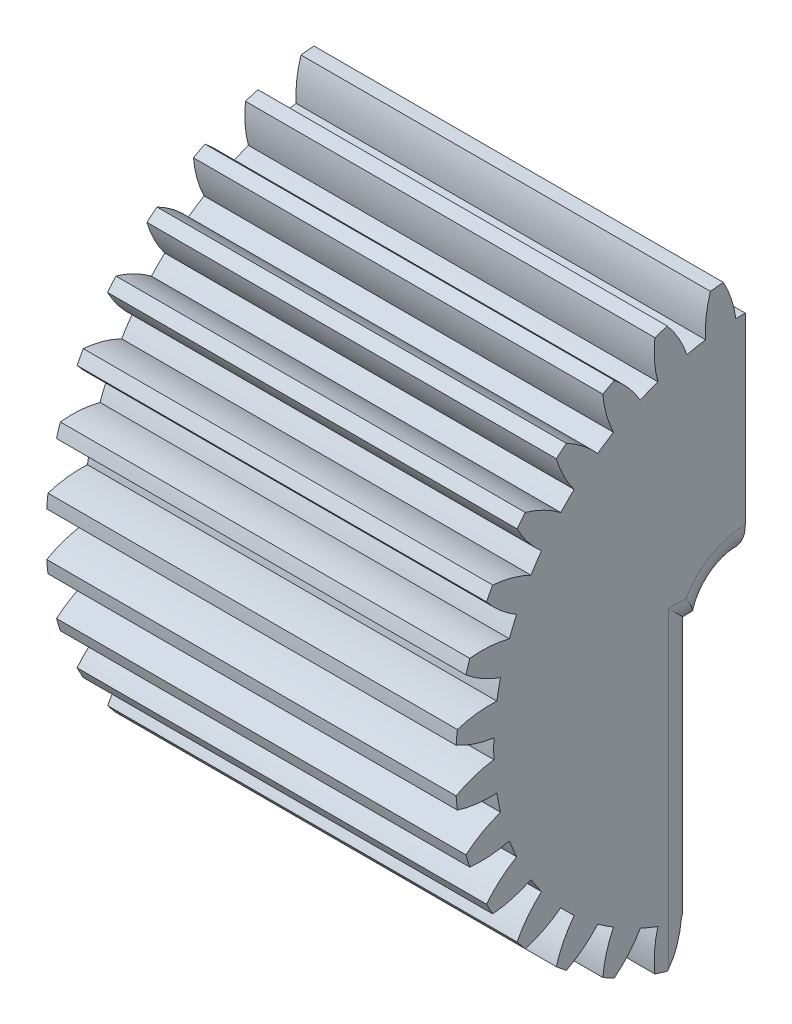
SolidWorks part; units mm, degrees
ref_plane "Plane1" through (0, 0, 0) normal (0, 0, 1) x (1, 0, 0)
ref_plane "Plane2" through (0, 0, 0) normal (0, 1, 0) x (1, 0, 0)
ref_plane "Plane3" through (0, 0, 0) normal (1, 0, 0) x (0, 0, -1)
other "Configuration Table"
sketch "HoldingSke" plane through (0, 0, 0) normal (0, 1, 0) x (1, 0, 0)
  line L0 (0, 0) -> (1.6961, -1.0598)
  line L1 (-15, 0) -> (100, 0) construction
  line L2 (0, 0) -> (-2.1039, 2.3779)
  line L3 (0, 0) -> (-11.863, 4.5341)
  line L4 (0, 0) -> (7.3237, 4.5764)
  line L5 (0, 0) -> (-46.8476, -17.4728)
  line L6 (0, 0) -> (-8.2896, -5.593)
  line L7 (-2.1039, 2.3779) -> (8.6586, 51.2059)
  line L8 (-76.2, 54.61) -> (-75.9, 54.61)
  line L9 (-67.7845, 28.3722) -> (-49.3413, 33.142)
  line L10 (-76.2, 71.12) -> (104.1128, 71.12)
  line L11 (0, 0) -> (-10, 0)
  line L12 (-76.2, 101.6) -> (-76.181, 101.6)
  line L13 (24.9733, 27.94) -> (52.9518, 28.4284)
  line L14 (24.9733, 27.94) -> (24.9743, 27.94)
  line L15 (24.9733, 27.94) -> (100.4006, 29.5858)
  line L16 (-63.627, -0.5) -> (-12.827, -0.5)
  circle A0 centre (0, 0) radius 1
  circle A1 centre (0, 0) radius 7.374
  circle A2 centre (0, 0) radius 37.5
  circle A3 centre (0, 0) radius 1
  dimension "MHD" = 14.748
  dimension "Hub_dia" = 75
  dimension "Bore" = 2
  dimension "MBD" = 2
  dimension "Num_teeth" = 32
  dimension "Pitch" = 2
  dimension "Overall_len" = 50
  dimension "Show_teeth" = 32
  dimension "Thickness" = 10
  dimension "OAL" = 50.0001
  dimension "T_dim" = 0.3
  dimension "Ap" = 14.5
  dimension "H" = 19.05
  dimension "Pitch_radius" = 180.3128
  dimension "Width" = 10
  dimension "Backlash" = 0.019
  dimension "Addendum_fac" = 1
  dimension "Dedendum_fac" = 1.25
  dimension "Clearance_fac" = 0.25
  dimension "Dedendum_add" = 0.001
  dimension "Module" = 0.5
sketch "BasProSke" plane through (0, 0, 0) normal (0, 1, 0) x (1, 0, 0)
  line L0 (-10, 0) -> (60, 0) construction
  line L1 (0, 0) -> (0, 8.5)
  line L2 (0, 0) -> (10, 0)
  line L3 (10, 0) -> (10, 8.5)
  line L4 (10, 8.5) -> (0, 8.5)
  dimension "Thickness" = 10
  dimension "Diameter" = 17
revolve "Base-Revolve" add sketch "BasProSke" angle 360 about L0
sketch "TooCutSke" plane through (0, 0, 0) normal (1, 0, 0) x (0, 0, -1)
  line L1 (0, 0) -> (0, 107) construction
  line L2 (0, 0) -> (-0.4258, 7.9887) construction
  line L3 (0, 0) -> (-1.5667, 15.9069) construction
  line L4 (-0.4258, 7.9887) -> (-0.7833, 7.9534) construction
  arc A0 (0.277, 7.3688) -> (-0.277, 7.3688) centre (0, 0) ccw
  arc A1 (0.6561, 8.5001) -> (-0.6561, 8.5001) centre (0, 0) ccw
  circle A2 centre (0, 0) radius 8 construction
  circle A3 centre (0, 0) radius 7.7452 construction
  arc A4 (-0.277, 7.3688) -> (-0.6561, 8.5001) centre (-3.4475, 6.9356) ccw
  arc A5 (0.6561, 8.5001) -> (0.277, 7.3688) centre (3.4475, 6.9356) ccw
  dimension "Root_dia" = 14.748
  dimension "Overcut_dia" = 17.0508
  dimension "Pitch_dia" = 16
  dimension "Base_dia" = 15.4904
  dimension "Flank_rad" = 3.2
  dimension "Half_ang" = 5.625
  dimension "Half_CT" = 0.3593
extrude "ToothCut" cut sketch "TooCutSke" along normal through all
fillet "Breaks" [suppressed] radius 0.01
fillet "RootFillets" [suppressed] radius 0.126
pattern_circular "TeethCuts" count 32 every 11.25 about axis through (-10, 0, 0) along (1, 0, 0) of "ToothCut", "RootFillets", "Breaks"
sketch "HubNeaOneSke" plane through (0, 0, 0) normal (-1, 0, 0) x (0, 0, 1)
  circle A0 centre (0, 0) radius 7.374
  dimension "Diameter" = 14.748
extrude "HubNearOne" [suppressed] add sketch "HubNeaOneSke" along normal blind 40.0001
sketch "HubNeaBotSke" plane through (0, 0, 0) normal (-1, 0, 0) x (0, 0, 1)
  circle A0 centre (0, 0) radius 7.374
  dimension "Diameter" = 14.748
extrude "HubNearBoth" [suppressed] add sketch "HubNeaBotSke" along normal blind 20
ref_plane "FarPln" through (10, 0, 0) normal (1, 0, 0) x (0, 0, -1)
sketch "HubFarSke" plane through (10, 0, 0) normal (1, 0, 0) x (0, 0, -1)
  circle A0 centre (0, 0) radius 7.374
  dimension "Diameter" = 14.748
extrude "HubFar" [suppressed] add sketch "HubFarSke" along normal blind 20
sketch "BorSke" plane through (0, 0, 0) normal (1, 0, 0) x (0, 0, -1)
  circle A0 centre (0, 0) radius 1
  dimension "Diameter" = 2
extrude "Bore" cut sketch "BorSke" along normal mid plane 100.0001
sketch "KeySke" plane through (0, 0, 0) normal (1, 0, 0) x (0, 0, -1)
  line L0 (-0.4, 0) -> (-0.4, 1.3)
  line L1 (-0.4, 1.3) -> (0.4, 1.3)
  line L2 (0.4, 1.3) -> (0.4, 0)
  line L3 (0, 0) -> (0, 34) construction
  line L4 (-0.4, 0) -> (0.4, 0)
  dimension "Offset" = 1.3
  dimension "Width" = 0.8
extrude "Keyway" [suppressed] cut sketch "KeySke" along normal mid plane 100.0001
pattern_circular "Keyway2" [suppressed] count 2 every 90 about axis through (-10, 0, 0) along (1, 0, 0)
sketch "Sketch1" plane through (10, 0, 0) normal (1, 0, 0) x (0, 0, -1)
  line L1 (-1.1, 0) -> (1.1, 0)
  line L2 (-1.1, 0) -> (-1.1, -12)
  line L3 (-1.1, -12) -> (1.1, -12)
  line L4 (1.1, 0) -> (1.1, -12)
  circle A0 centre (0, 0) radius 1 construction
  dimension "D3" = 12
  dimension "D1" = 2.2
  dimension "D2" = 1.1
  dimension "D4" = 12
extrude "Cut-Extrude1" cut sketch "Sketch1" against normal through all
sketch "Sketch2" plane through (0, 0, 0) normal (0, 0, 1) x (1, 0, 0)
  line L3 (3.25, 0) -> (8.75, 0)
  arc A0 (8.75, 0) -> (3.25, 0) centre (6, 0) ccw
  dimension "D2" = 5.5
  dimension "D1" = 6
revolve "Cut-Revolve1" cut sketch "Sketch2" angle 360 about L3
ref_plane "Plane4" through (3, 0, 0) normal (-1, 0, 0) x (0, 0, 1)
sketch "Sketch4" plane through (3, 0, 0) normal (-1, 0, 0) x (0, 0, 1)
  circle A0 centre (0, 0) radius 1.125
  circle A1 centre (0, 0) radius 0.5
  dimension "D1" = 1
extrude "Boss-Extrude1" add sketch "Sketch4" along normal blind 0.5
sketch "Sketch5" plane through (0, 0, -1.1) normal (0, 0, 1) x (1, 0, 0)
  line L0 (0, -8.1488) -> (10, -8.1488) construction
  line L1 (0, 0) -> (2.5, 0)
  line L2 (0, 0) -> (0, -8.1488)
  line L3 (0, -8.1488) -> (2.5, -8.1488)
  line L4 (2.5, 0) -> (2.5, -8.1488)
  dimension "D1" = 2.5
extrude "Boss-Extrude2" add sketch "Sketch5" along normal up to next
sketch "Sketch6" plane through (0, 0, 0) normal (-1, 0, 0) x (0, 0, 1)
  line L0 (1, 0) -> (-1, 0) construction
  circle A0 centre (0, 0) radius 2.25
  dimension "D1" = 4.5
extrude "Cut-Extrude4" cut sketch "Sketch6" against normal blind 2.45
sketch "Sketch7" plane through (2.5, 0, 0) normal (1, 0, 0) x (0, 0, -1)
  circle A0 centre (0, 0) radius 0.5
extrude "Cut-Extrude5" cut sketch "Sketch7" against normal blind 2.4
sketch "Sketch8" plane through (0, 0, 0) normal (0, 0, 1) x (1, 0, 0)
  line L0 (0, 0.277) -> (0, -0.277) construction
  line L1 (-0.5, 9) -> (10.5, 9)
  line L2 (-0.5, 9) -> (-0.5, -9)
  line L3 (-0.5, -9) -> (10.5, -9)
  line L4 (10.5, 9) -> (10.5, -9)
  point P6 (0, 0)
  dimension "D1" = 11
  dimension "D2" = 18
  dimension "D3" = 0.5
  dimension "D4" = 9
extrude "Cut-Extrude6" cut sketch "Sketch8" against normal blind 10
sketch "Sketch9" plane through (0, 0, 0) normal (0, 0, -1) x (-1, 0, 0)
  line L0 (-10, 1) -> (-10, 7.374) construction
  line L1 (-8.5, 5.75) -> (-6.5, 5.75)
  line L2 (-8.5, 5.75) -> (-8.5, 3.75)
  line L3 (-8.5, 3.75) -> (-6.5, 3.75)
  line L4 (-6.5, 5.75) -> (-6.5, 3.75)
  line L5 (-3.5, 5.75) -> (-1.5, 5.75)
  line L6 (-3.5, 5.75) -> (-3.5, 3.75)
  line L7 (-3.5, 3.75) -> (-1.5, 3.75)
  line L8 (-1.5, 5.75) -> (-1.5, 3.75)
  line L9 (0, -2.25) -> (0, 2.25) construction
  line L10 (0, 7.374) -> (0, 2.25) construction
  point P12 (0, 0)
  dimension "D1" = 2
  dimension "D2" = 2
  dimension "D3" = 2
  dimension "D4" = 2
  dimension "D5" = 1.5
  dimension "D6" = 3.75
  dimension "D7" = 3.75
  dimension "D8" = 1.5
extrude "Boss-Extrude3" add sketch "Sketch9" along normal blind 2
sketch "Sketch10" plane through (10, 0, 0) normal (1, 0, 0) x (0, 0, -1)
  line L1 (0, 0) -> (-1.25, 0)
  line L2 (0, 0) -> (0, -9)
  line L3 (0, -9) -> (-1.25, -9)
  line L4 (-1.25, 0) -> (-1.25, -9)
  dimension "D1" = 1.25
  dimension "D2" = 9
extrude "Cut-Extrude7" cut sketch "Sketch10" against normal blind 7
ref_plane "Plane5" through (12, 0, 0) normal (1, 0, 0) x (0, 0, -1)
sketch "Sketch11" plane through (12, 0, 0) normal (1, 0, 0) x (0, 0, -1)
  line L0 (-1.25, 0) -> (-1.25, -7.2673) construction
  line L1 (-1, 0) -> (-1.25, 0) construction
  line L2 (0, 1) -> (0, 7.374) construction
  line L3 (-1.25, 0) -> (-1.25, -7.2673)
  line L4 (-1, 0) -> (-1.25, 0)
  line L5 (0, 1) -> (0, 7.374)
  arc A0 (-2.2837, 8.1875) -> (-2.6499, 8.0764) centre (0, 0) ccw construction
  arc A1 (-0.6425, 8.4757) -> (-1.0233, 8.4382) centre (0, 0) ccw construction
  arc A2 (-1.1659, 7.2812) -> (-1.7093, 7.1732) centre (0, 0) ccw construction
  arc A3 (-3.8371, 7.5846) -> (-4.1746, 7.4042) centre (0, 0) ccw construction
  arc A4 (-2.564, 6.9139) -> (-3.0758, 6.7019) centre (0, 0) ccw construction
  arc A5 (-3.8636, 6.2808) -> (-4.3242, 5.973) centre (0, 0) ccw construction
  arc A6 (-5.2431, 6.6903) -> (-5.5389, 6.4475) centre (0, 0) ccw construction
  arc A7 (-5.0147, 5.4064) -> (-5.4064, 5.0147) centre (0, 0) ccw construction
  arc A8 (-6.4475, 5.5389) -> (-6.6903, 5.2431) centre (0, 0) ccw construction
  arc A9 (-7.4042, 4.1746) -> (-7.5846, 3.8371) centre (0, 0) ccw construction
  arc A10 (-5.973, 4.3242) -> (-6.2808, 3.8636) centre (0, 0) ccw construction
  arc A11 (-6.7019, 3.0758) -> (-6.9139, 2.564) centre (0, 0) ccw construction
  arc A12 (-8.0764, 2.6499) -> (-8.1875, 2.2837) centre (0, 0) ccw construction
  arc A13 (-7.1732, 1.7093) -> (-7.2812, 1.1659) centre (0, 0) ccw construction
  arc A14 (-8.4382, 1.0233) -> (-8.4757, 0.6425) centre (0, 0) ccw construction
  arc A15 (-7.3688, 0.277) -> (-7.3688, -0.277) centre (0, 0) ccw construction
  arc A16 (-8.4757, -0.6425) -> (-8.4382, -1.0233) centre (0, 0) ccw construction
  arc A17 (-7.2812, -1.1659) -> (-7.1732, -1.7093) centre (0, 0) ccw construction
  arc A18 (-8.1875, -2.2837) -> (-8.0764, -2.6499) centre (0, 0) ccw construction
  arc A19 (-6.9139, -2.564) -> (-6.7019, -3.0758) centre (0, 0) ccw construction
  arc A20 (-7.5846, -3.8371) -> (-7.4042, -4.1746) centre (0, 0) ccw construction
  arc A21 (-6.2808, -3.8636) -> (-5.973, -4.3242) centre (0, 0) ccw construction
  arc A22 (-6.6903, -5.2431) -> (-6.4475, -5.5389) centre (0, 0) ccw construction
  arc A23 (-5.4064, -5.0147) -> (-5.0147, -5.4064) centre (0, 0) ccw construction
  arc A24 (-5.5389, -6.4475) -> (-5.2431, -6.6903) centre (0, 0) ccw construction
  arc A25 (-4.3242, -5.973) -> (-3.8636, -6.2808) centre (0, 0) ccw construction
  arc A26 (-4.1746, -7.4042) -> (-3.8371, -7.5846) centre (0, 0) ccw construction
  arc A27 (-3.0758, -6.7019) -> (-2.564, -6.9139) centre (0, 0) ccw construction
  arc A28 (-1.7093, -7.1732) -> (-1.25, -7.2673) centre (0, 0) ccw construction
  arc A29 (-2.6499, -8.0764) -> (-2.2837, -8.1875) centre (0, 0) ccw construction
  arc A30 (-2.2837, -8.1875) -> (-1.7093, -7.1732) centre (-4.7344, -6.1297) ccw construction
  arc A31 (-2.564, -6.9139) -> (-2.6499, -8.0764) centre (0.531, -7.727) ccw construction
  arc A32 (-3.8371, -7.5846) -> (-3.0758, -6.7019) centre (-5.8392, -5.0883) ccw construction
  arc A33 (-3.8636, -6.2808) -> (-4.1746, -7.4042) centre (-0.9867, -7.6821) ccw construction
  arc A34 (-5.2431, -6.6903) -> (-4.3242, -5.973) centre (-6.7197, -3.8514) ccw construction
  arc A35 (-5.0147, -5.4064) -> (-5.5389, -6.4475) centre (-2.4664, -7.342) ccw construction
  arc A36 (-6.4475, -5.5389) -> (-5.4064, -5.0147) centre (-7.342, -2.4664) ccw construction
  arc A37 (-5.973, -4.3242) -> (-6.6903, -5.2431) centre (-3.8514, -6.7197) ccw construction
  arc A38 (-7.4042, -4.1746) -> (-6.2808, -3.8636) centre (-7.6821, -0.9867) ccw construction
  arc A39 (-6.7019, -3.0758) -> (-7.5846, -3.8371) centre (-5.0883, -5.8392) ccw construction
  arc A40 (-8.0764, -2.6499) -> (-6.9139, -2.564) centre (-7.727, 0.531) ccw construction
  arc A41 (-7.1732, -1.7093) -> (-8.1875, -2.2837) centre (-6.1297, -4.7344) ccw construction
  arc A42 (-8.4382, -1.0233) -> (-7.2812, -1.1659) centre (-7.4749, 2.0282) ccw construction
  arc A43 (-7.3688, -0.277) -> (-8.4757, -0.6425) centre (-6.9356, -3.4475) ccw construction
  arc A44 (-8.4757, 0.6425) -> (-7.3688, 0.277) centre (-6.9356, 3.4475) ccw construction
  arc A45 (-7.2812, 1.1659) -> (-8.4382, 1.0233) centre (-7.4749, -2.0282) ccw construction
  arc A46 (-8.1875, 2.2837) -> (-7.1732, 1.7093) centre (-6.1297, 4.7344) ccw construction
  arc A47 (-6.9139, 2.564) -> (-8.0764, 2.6499) centre (-7.727, -0.531) ccw construction
  arc A48 (-7.5846, 3.8371) -> (-6.7019, 3.0758) centre (-5.0883, 5.8392) ccw construction
  arc A49 (-6.2808, 3.8636) -> (-7.4042, 4.1746) centre (-7.6821, 0.9867) ccw construction
  arc A50 (-6.6903, 5.2431) -> (-5.973, 4.3242) centre (-3.8514, 6.7197) ccw construction
  arc A51 (-5.4064, 5.0147) -> (-6.4475, 5.5389) centre (-7.342, 2.4664) ccw construction
  arc A52 (-5.5389, 6.4475) -> (-5.0147, 5.4064) centre (-2.4664, 7.342) ccw construction
  arc A53 (-4.3242, 5.973) -> (-5.2431, 6.6903) centre (-6.7197, 3.8514) ccw construction
  arc A54 (-4.1746, 7.4042) -> (-3.8636, 6.2808) centre (-0.9867, 7.6821) ccw construction
  arc A55 (-3.0758, 6.7019) -> (-3.8371, 7.5846) centre (-5.8392, 5.0883) ccw construction
  arc A56 (-2.6499, 8.0764) -> (-2.564, 6.9139) centre (0.531, 7.727) ccw construction
  arc A57 (-1.7093, 7.1732) -> (-2.2837, 8.1875) centre (-4.7344, 6.1297) ccw construction
  arc A58 (-1.0233, 8.4382) -> (-1.1659, 7.2812) centre (2.0282, 7.4749) ccw construction
  arc A59 (-0.277, 7.3688) -> (-0.6425, 8.4757) centre (-3.4475, 6.9356) ccw construction
  arc A60 (0, 7.374) -> (-0.277, 7.3688) centre (0, 0) ccw construction
  arc A61 (0, 1) -> (-1, 0) centre (0, 0) ccw construction
  arc A62 (-2.2837, 8.1875) -> (-2.6499, 8.0764) centre (0, 0) ccw
  arc A63 (-0.6425, 8.4757) -> (-1.0233, 8.4382) centre (0, 0) ccw
  arc A64 (-1.1659, 7.2812) -> (-1.7093, 7.1732) centre (0, 0) ccw
  arc A65 (-3.8371, 7.5846) -> (-4.1746, 7.4042) centre (0, 0) ccw
  arc A66 (-2.564, 6.9139) -> (-3.0758, 6.7019) centre (0, 0) ccw
  arc A67 (-3.8636, 6.2808) -> (-4.3242, 5.973) centre (0, 0) ccw
  arc A68 (-5.2431, 6.6903) -> (-5.5389, 6.4475) centre (0, 0) ccw
  arc A69 (-5.0147, 5.4064) -> (-5.4064, 5.0147) centre (0, 0) ccw
  arc A70 (-6.4475, 5.5389) -> (-6.6903, 5.2431) centre (0, 0) ccw
  arc A71 (-7.4042, 4.1746) -> (-7.5846, 3.8371) centre (0, 0) ccw
  arc A72 (-5.973, 4.3242) -> (-6.2808, 3.8636) centre (0, 0) ccw
  arc A73 (-6.7019, 3.0758) -> (-6.9139, 2.564) centre (0, 0) ccw
  arc A74 (-8.0764, 2.6499) -> (-8.1875, 2.2837) centre (0, 0) ccw
  arc A75 (-7.1732, 1.7093) -> (-7.2812, 1.1659) centre (0, 0) ccw
  arc A76 (-8.4382, 1.0233) -> (-8.4757, 0.6425) centre (0, 0) ccw
  arc A77 (-7.3688, 0.277) -> (-7.3688, -0.277) centre (0, 0) ccw
  arc A78 (-8.4757, -0.6425) -> (-8.4382, -1.0233) centre (0, 0) ccw
  arc A79 (-7.2812, -1.1659) -> (-7.1732, -1.7093) centre (0, 0) ccw
  arc A80 (-8.1875, -2.2837) -> (-8.0764, -2.6499) centre (0, 0) ccw
  arc A81 (-6.9139, -2.564) -> (-6.7019, -3.0758) centre (0, 0) ccw
  arc A82 (-7.5846, -3.8371) -> (-7.4042, -4.1746) centre (0, 0) ccw
  arc A83 (-6.2808, -3.8636) -> (-5.973, -4.3242) centre (0, 0) ccw
  arc A84 (-6.6903, -5.2431) -> (-6.4475, -5.5389) centre (0, 0) ccw
  arc A85 (-5.4064, -5.0147) -> (-5.0147, -5.4064) centre (0, 0) ccw
  arc A86 (-5.5389, -6.4475) -> (-5.2431, -6.6903) centre (0, 0) ccw
  arc A87 (-4.3242, -5.973) -> (-3.8636, -6.2808) centre (0, 0) ccw
  arc A88 (-4.1746, -7.4042) -> (-3.8371, -7.5846) centre (0, 0) ccw
  arc A89 (-3.0758, -6.7019) -> (-2.564, -6.9139) centre (0, 0) ccw
  arc A90 (-1.7093, -7.1732) -> (-1.25, -7.2673) centre (0, 0) ccw
  arc A91 (-2.6499, -8.0764) -> (-2.2837, -8.1875) centre (0, 0) ccw
  arc A92 (-2.2837, -8.1875) -> (-1.7093, -7.1732) centre (-4.7344, -6.1297) ccw
  arc A93 (-2.564, -6.9139) -> (-2.6499, -8.0764) centre (0.531, -7.727) ccw
  arc A94 (-3.8371, -7.5846) -> (-3.0758, -6.7019) centre (-5.8392, -5.0883) ccw
  arc A95 (-3.8636, -6.2808) -> (-4.1746, -7.4042) centre (-0.9867, -7.6821) ccw
  arc A96 (-5.2431, -6.6903) -> (-4.3242, -5.973) centre (-6.7197, -3.8514) ccw
  arc A97 (-5.0147, -5.4064) -> (-5.5389, -6.4475) centre (-2.4664, -7.342) ccw
  arc A98 (-6.4475, -5.5389) -> (-5.4064, -5.0147) centre (-7.342, -2.4664) ccw
  arc A99 (-5.973, -4.3242) -> (-6.6903, -5.2431) centre (-3.8514, -6.7197) ccw
  arc A100 (-7.4042, -4.1746) -> (-6.2808, -3.8636) centre (-7.6821, -0.9867) ccw
  arc A101 (-6.7019, -3.0758) -> (-7.5846, -3.8371) centre (-5.0883, -5.8392) ccw
  arc A102 (-8.0764, -2.6499) -> (-6.9139, -2.564) centre (-7.727, 0.531) ccw
  arc A103 (-7.1732, -1.7093) -> (-8.1875, -2.2837) centre (-6.1297, -4.7344) ccw
  arc A104 (-8.4382, -1.0233) -> (-7.2812, -1.1659) centre (-7.4749, 2.0282) ccw
  arc A105 (-7.3688, -0.277) -> (-8.4757, -0.6425) centre (-6.9356, -3.4475) ccw
  arc A106 (-8.4757, 0.6425) -> (-7.3688, 0.277) centre (-6.9356, 3.4475) ccw
  arc A107 (-7.2812, 1.1659) -> (-8.4382, 1.0233) centre (-7.4749, -2.0282) ccw
  arc A108 (-8.1875, 2.2837) -> (-7.1732, 1.7093) centre (-6.1297, 4.7344) ccw
  arc A109 (-6.9139, 2.564) -> (-8.0764, 2.6499) centre (-7.727, -0.531) ccw
  arc A110 (-7.5846, 3.8371) -> (-6.7019, 3.0758) centre (-5.0883, 5.8392) ccw
  arc A111 (-6.2808, 3.8636) -> (-7.4042, 4.1746) centre (-7.6821, 0.9867) ccw
  arc A112 (-6.6903, 5.2431) -> (-5.973, 4.3242) centre (-3.8514, 6.7197) ccw
  arc A113 (-5.4064, 5.0147) -> (-6.4475, 5.5389) centre (-7.342, 2.4664) ccw
  arc A114 (-5.5389, 6.4475) -> (-5.0147, 5.4064) centre (-2.4664, 7.342) ccw
  arc A115 (-4.3242, 5.973) -> (-5.2431, 6.6903) centre (-6.7197, 3.8514) ccw
  arc A116 (-4.1746, 7.4042) -> (-3.8636, 6.2808) centre (-0.9867, 7.6821) ccw
  arc A117 (-3.0758, 6.7019) -> (-3.8371, 7.5846) centre (-5.8392, 5.0883) ccw
  arc A118 (-2.6499, 8.0764) -> (-2.564, 6.9139) centre (0.531, 7.727) ccw
  arc A119 (-1.7093, 7.1732) -> (-2.2837, 8.1875) centre (-4.7344, 6.1297) ccw
  arc A120 (-1.0233, 8.4382) -> (-1.1659, 7.2812) centre (2.0282, 7.4749) ccw
  arc A121 (-0.277, 7.3688) -> (-0.6425, 8.4757) centre (-3.4475, 6.9356) ccw
  arc A122 (0, 7.374) -> (-0.277, 7.3688) centre (0, 0) ccw
  arc A123 (0, 1) -> (-1, 0) centre (0, 0) ccw
extrude "Boss-Extrude4" add sketch "Sketch11" against normal up to next
fillet "Fillet2" radius 1 3 edges at (12, -3.6336, 1.25) (12, 0, 1.125) (12, 0.7071, 0.7071)
equation "' \"Module@HoldingSke\" = 6.35"
equation "' \"Num_teeth@HoldingSke\" = 12"
equation "' \"Ap@HoldingSke\" =  20"
equation "' \"Ap@HoldingSke\" = 20"
equation "' \"Width@HoldingSke\" = 0.5 * 25.4"
equation "' \"Hub_dia@HoldingSke\"= 1 * 25.4"
equation "' \"Hub_dia@HoldingSke\" = 1 * 25.4"
equation "' \"Overall_len@HoldingSke\" = 1.0 * 25.4"
equation "' \"Bore@HoldingSke\" = 0.75 * 25.4"
equation "' \"T_dim@HoldingSke\" = 0.1 * 25.4"
equation "' \"Width@KeySke\" = 0.25 * 25.4"
equation "' \"Show_teeth@HoldingSke\" = 13"
equation "' \"Backlash@HoldingSke\" = 0.009 * 25.4"
equation "' \"Addendum_fac@HoldingSke\" = 1.0"
equation "' \"Dedendum_fac@HoldingSke\" = 1.25"
equation "' \"Dedendum_add@HoldingSke\" = 0.00005 * 25.4"
equation "' \"Clearance_fac@HoldingSke\" = 0.25"
equation "\"Pitch@HoldingSke\" = 1 / \"Module@HoldingSke\""
equation "\"Overcut_dia@TooCutSke\" = (\"Num_teeth@HoldingSke\" + 2 * \"Addendum_fac@HoldingSke\") / \"Pitch@HoldingSke\" + 0.002 * 25.4"
equation "\"Pitch_dia@TooCutSke\" = \"Num_teeth@HoldingSke\" / \"Pitch@HoldingSke\""
equation "\"Base_dia@TooCutSke\" = \"Num_teeth@HoldingSke\" / \"Pitch@HoldingSke\" * cos((\"Ap@HoldingSke\"  * 3.14159265 / 180))"
equation "\"Root_dia@TooCutSke\" = (\"Num_teeth@HoldingSke\" + 2) / \"Pitch@HoldingSke\" - 2 * (\"Addendum_fac@HoldingSke\" + \"Dedendum_fac@HoldingSke\") / \"Pitch@HoldingSke\" - \"Dedendum_add@HoldingSke\" * 2"
equation "\"Half_ang@TooCutSke\" = 180 / \"Num_teeth@HoldingSke\""
equation "\"Half_CT@TooCutSke\" = \"Num_teeth@HoldingSke\" / \"Pitch@HoldingSke\" * sin((3.14159265 / 2 / \"Num_teeth@HoldingSke\")) / 2 - 7 * \"Backlash@HoldingSke\" / 4"
equation "\"Flank_rad@TooCutSke\" = \"Num_teeth@HoldingSke\" / \"Pitch@HoldingSke\" / 5"
equation "\"Radius@RootFillets\" = \"Clearance_fac@HoldingSke\" / \"Pitch@HoldingSke\" + \"Dedendum_add@HoldingSke\""
equation "\"Break_rad@Breaks\" = 0.02 / \"Pitch@HoldingSke\""
equation "\"Thickness@HoldingSke\" = \"Width@HoldingSke\""
equation "\"OAL@HoldingSke\" = \"Thickness@HoldingSke\""
equation "\"MHD@HoldingSke\" = (\"Num_teeth@HoldingSke\" + 2) / \"Pitch@HoldingSke\" - 2 * (\"Addendum_fac@HoldingSke\" + \"Dedendum_fac@HoldingSke\")  / \"Pitch@HoldingSke\" - \"Dedendum_add@HoldingSke\" * 2"
equation "\"MBD@HoldingSke\" = (\"Num_teeth@HoldingSke\" + 2) / \"Pitch@HoldingSke\" - 2 * (\"Addendum_fac@HoldingSke\" + \"Dedendum_fac@HoldingSke\")  / \"Pitch@HoldingSke\" - \"Dedendum_add@HoldingSke\" * 2 - 0.002 * 25.4"
equation "\"MHD@HoldingSke\" = ((sgn( \"MHD@HoldingSke\" - \"Hub_dia@HoldingSke\" )-1)*( \"MHD@HoldingSke\" - \"Hub_dia@HoldingSke\" ))/-2+ \"Hub_dia@HoldingSke\""
equation "\"MBD@HoldingSke\" = ((sgn( \"MBD@HoldingSke\" - \"Bore@HoldingSke\" )-1)*( \"MBD@HoldingSke\" - \"Bore@HoldingSke\" ))/-2+ \"Bore@HoldingSke\""
equation "\"OAL@HoldingSke\" = ((sgn( \"OAL@HoldingSke\" - \"Overall_len@HoldingSke\" )+1)*( \"OAL@HoldingSke\" - \"Overall_len@HoldingSke\" ))/2 + \"Overall_len@HoldingSke\" + 0.000002 * 25.4"
equation "\"Num_teeth@TeethCuts\" = int( \"Show_teeth@HoldingSke\" ) + 1"
equation "\"Num_teeth@TeethCuts\" = ((sgn( \"Num_teeth@TeethCuts\" - \"Num_teeth@HoldingSke\" )-1)*( \"Num_teeth@TeethCuts\" - \"Num_teeth@HoldingSke\" ))/-2+ \"Num_teeth@HoldingSke\""
equation "\"Num_teeth@TeethCuts\" = ((sgn( \"Num_teeth@TeethCuts\" - 2.0)+1)*( \"Num_teeth@TeethCuts\" - 2.0))/2 +2.0"
equation "\"Angle@TeethCuts\" = 360.0 / \"Num_teeth@HoldingSke\""
equation "\"Diameter@BasProSke\" = (\"Num_teeth@HoldingSke\" + 2 * \"Addendum_fac@HoldingSke\") / \"Pitch@HoldingSke\""
equation "\"Thickness@BasProSke\"  = \"Thickness@HoldingSke\""
equation "' \"Fillet_rad@BasProSke\" =  \"Thickness@HoldingSke\" * 0.05"
equation "' \"Fillet_rad@BasProSke\" = \"Thickness@HoldingSke\" * 0.05"
equation "\"MHD@HoldingSke\" = ((sgn( \"MHD@HoldingSke\" - \"Root_dia@TooCutSke\" )-1)*( \"MHD@HoldingSke\" - \"Root_dia@TooCutSke\" ))/-2+ \"Root_dia@TooCutSke\""
equation "\"Diameter@HubNeaOneSke\" = \"MHD@HoldingSke\""
equation "\"Length@HubNearOne\" = \"OAL@HoldingSke\" - \"Thickness@BasProSke\""
equation "\"Diameter@HubNeaBotSke\" = \"MHD@HoldingSke\""
equation "\"Length@HubNearBoth\" = ( \"OAL@HoldingSke\" - \"Thickness@BasProSke\" ) / 2.0"
equation "\"Thickness@FarPln\" = \"Thickness@BasProSke\""
equation "\"Diameter@HubFarSke\" = \"MHD@HoldingSke\""
equation "\"Length@HubFar\" = ( \"OAL@HoldingSke\" - \"Thickness@BasProSke\" ) / 2.0"
equation "\"Diameter@BorSke\" = \"MBD@HoldingSke\""
equation "\"D1@Bore\" = \"OAL@HoldingSke\" * 2.0"
equation "\"D1@Keyway\" = \"OAL@HoldingSke\" * 2.0"
equation "\"Offset@KeySke\" = \"T_dim@HoldingSke\" + \"MBD@HoldingSke\" / 2.0"
